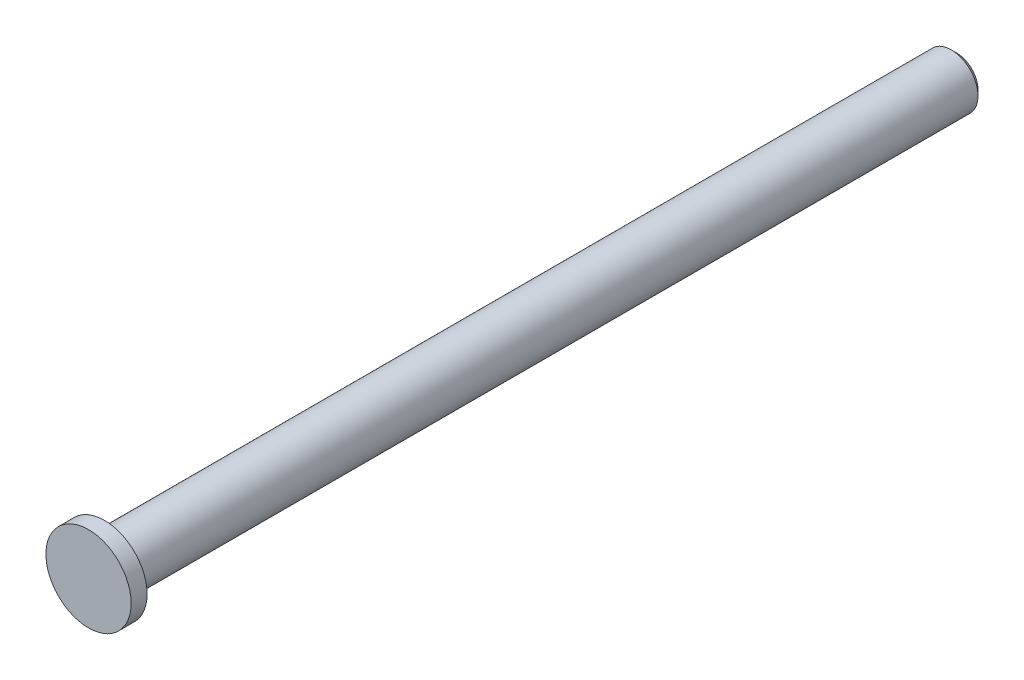
SolidWorks part; units mm, degrees
ref_plane "Front Plane" through (0, 0, 0) normal (0, 0, 1) x (1, 0, 0)
ref_plane "Top Plane" through (0, 0, 0) normal (0, 1, 0) x (1, 0, 0)
ref_plane "Right Plane" through (0, 0, 0) normal (1, 0, 0) x (0, 0, -1)
sketch "Sketch3" plane through (0, 0, 0) normal (0, 0, 1) x (1, 0, 0)
  circle A0 centre (0, 0) radius 4
  dimension "D1" = 8
extrude "Boss-Extrude3" add sketch "Sketch3" along normal blind 1.5
sketch "Sketch4" plane through (0, 0, 0) normal (0, 0, -1) x (-1, 0, 0)
  circle A0 centre (0, 0) radius 2.5
  dimension "D1" = 5
extrude "Boss-Extrude4" add sketch "Sketch4" along normal blind 80
chamfer "Chamfer2" distance 0.5 angle 45 1 edges at (-2.5, 0, -80)
